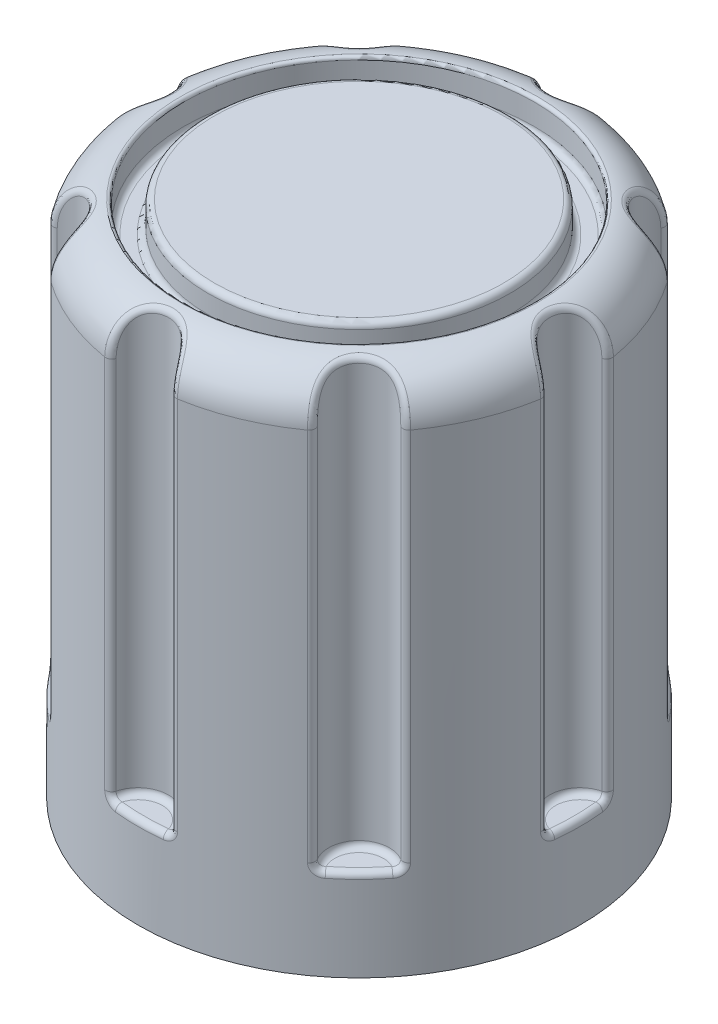
SolidWorks part; units mm, degrees
ref_plane "Plano frontal" through (0, 0, 0) normal (0, 0, 1) x (1, 0, 0)
ref_plane "Plano superior" through (0, 0, 0) normal (0, 1, 0) x (1, 0, 0)
ref_plane "Plano direito" through (0, 0, 0) normal (1, 0, 0) x (0, 0, -1)
sketch "Esboço1" plane through (0, 0, 0) normal (0, 1, 0) x (1, 0, 0)
  circle A0 centre (0, 0) radius 7.25
  dimension "D1" = 14.5
extrude "Ressalto-extrusão1" add sketch "Esboço1" along normal blind 17
fillet "Filete1" radius 1.5 1 edges at (0, 17, 7.25)
sketch "Esboço2" plane through (0, 17, 0) normal (0, 1, 0) x (1, 0, 0)
  circle A0 centre (0, 7.25) radius 1
  circle A1 centre (0, 0) radius 7.25 construction
  circle A2 centre (5.1265, 5.1265) radius 1
  circle A3 centre (7.25, 0) radius 1
  circle A4 centre (5.1265, -5.1265) radius 1
  circle A5 centre (0, -7.25) radius 1
  circle A6 centre (-5.1265, -5.1265) radius 1
  circle A7 centre (-7.25, 0) radius 1
  circle A8 centre (-5.1265, 5.1265) radius 1
  point P21 (0, 0)
  dimension "D2" = 2
  dimension "D1" = 8
extrude "Corte-extrusão1" cut sketch "Esboço2" against normal blind 14
sketch "Esboço3" plane through (0, 17, 0) normal (0, 1, 0) x (1, 0, 0)
  circle A0 centre (0, 0) radius 5.75
  circle A1 centre (0, 0) radius 4.95
  dimension "D1" = 0.8
extrude "Corte-extrusão2" cut sketch "Esboço3" against normal blind 1
fillet "Filete2" radius 0.2 2 edges at (0, 16, 5.75) (0, 16, 4.95)
fillet "Filete3" radius 0.2 1 edges at (0, 17, 4.95)
fillet "Filete4" radius 0.1 1 edges at (0, 17, 5.75)
sketch "Esboço4" plane through (0, 0, 0) normal (0, -1, 0) x (1, 0, 0)
  circle A0 centre (0, 0) radius 3.1
  dimension "D1" = 6.2
extrude "Corte-extrusão3" cut sketch "Esboço4" against normal blind 14
fillet "Filete5" radius 3 1 edges at (0, 14, -3.1)
fillet "Filete7" radius 0.2 40 edges at (7.25, 3, 0) (5.1265, 3, 5.1265) (0, 3, 7.25) (-5.1265, 3, 5.1265) (-7.25, 3, 0) (-5.1265, 3, -5.1265) (5.1265, 3, -5.1265) (0, 3, -7.25) (7.181, 9.25, -0.9976) (7.181, 9.25, 0.9976) (6.2503, 16.9141, -0.0247) (6.25, 3, 0) (5.7832, 9.25, 4.3723) (4.3723, 9.25, 5.7832) (4.4371, 16.9141, 4.4022) (4.4194, 3, 4.4194) (0.9976, 9.25, 7.181) (-0.9976, 9.25, 7.181) (0.0247, 16.9141, 6.2503) (0, 3, 6.25) (-4.3723, 9.25, 5.7832) (-5.7832, 9.25, 4.3723) (-4.4022, 16.9141, 4.4371) (-4.4194, 3, 4.4194) (-7.181, 9.25, 0.9976) (-7.181, 9.25, -0.9976) (-6.2503, 16.9141, 0.0247) (-6.25, 3, 0) (-5.7832, 9.25, -4.3723) (-4.3723, 9.25, -5.7832) (-4.4371, 16.9141, -4.4022) (-4.4194, 3, -4.4194) (4.3723, 9.25, -5.7832) (5.7832, 9.25, -4.3723) (4.4022, 16.9141, -4.4371) (4.4194, 3, -4.4194) (0.9976, 9.25, -7.181) (-0.9976, 9.25, -7.181) (-0.0247, 16.9141, -6.2503) (0, 3, -6.25)
